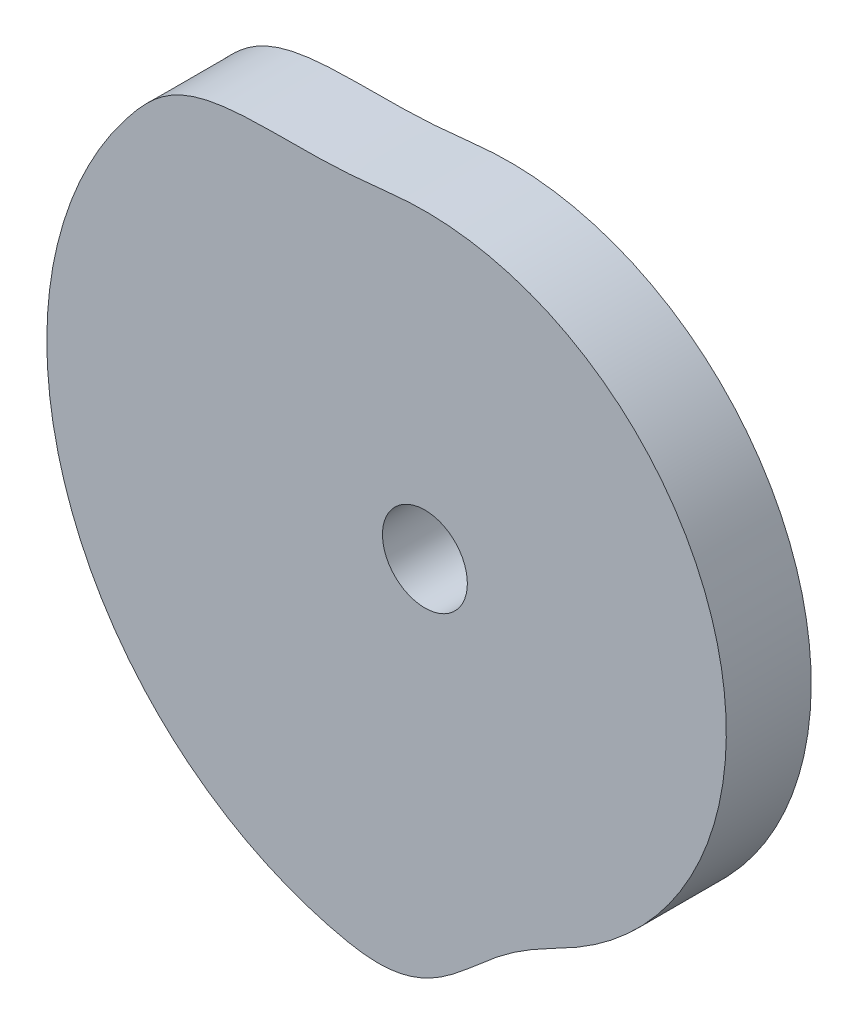
SolidWorks part; units mm, degrees
ref_plane "前视基准面" through (0, 0, 0) normal (0, 0, 1) x (1, 0, 0)
ref_plane "上视基准面" through (0, 0, 0) normal (0, 1, 0) x (1, 0, 0)
ref_plane "右视基准面" through (0, 0, 0) normal (1, 0, 0) x (0, 0, -1)
other "Configuration Table"
curve "曲线1"
sketch "草图1" plane through (0, 0, 0) normal (0, 0, 1) x (1, 0, 0)
  circle A0 centre (0, 0) radius 10
  spline S0 degree 3 poles (-56.2429, -69.0639) (-55.6381, -69.5522) (-55.029, -70.0349) (-54.4158, -70.5126) (-53.7983, -70.9847) (-53.1769, -71.4515) (-52.5513, -71.9128) (-51.9218, -72.3687) (-51.2882, -72.819) (-50.6509, -73.2638) (-50.0096, -73.7031) (-49.3645, -74.1366) (-48.7157, -74.5647) (-48.0631, -74.9868) (-47.4069, -75.4035) (-46.7471, -75.8142) (-46.0838, -76.2194) (-45.4169, -76.6186) (-44.7465, -77.0119) (-44.0728, -77.3996) (-43.3956, -77.7811) (-42.7153, -78.157) (-42.0315, -78.5266) (-41.3447, -78.8905) (-40.6547, -79.2483) (-39.9616, -79.6001) (-39.2654, -79.9458) (-38.5663, -80.2855) (-37.8642, -80.6188) (-37.1593, -80.9463) (-36.4515, -81.2674) (-35.7409, -81.5824) (-35.0276, -81.8912) (-34.3116, -82.1937) (-33.593, -82.49) (-32.8719, -82.7801) (-32.1483, -83.0638) (-31.4222, -83.3412) (-30.6937, -83.6121) (-29.9629, -83.8769) (-29.2298, -84.1352) (-28.4944, -84.3869) (-27.757, -84.6325) (-27.0174, -84.8715) (-26.2757, -85.104) (-25.532, -85.3299) (-24.7865, -85.5496) (-24.039, -85.7626) (-23.2896, -85.969) (-22.5385, -86.1691) (-21.786, -86.3624) (-21.034, -86.5486) (-20.2861, -86.7271) (-19.5453, -86.8959) (-18.8136, -87.0543) (-18.0909, -87.2016) (-17.3772, -87.3372) (-16.6721, -87.4607) (-15.9755, -87.5715) (-15.287, -87.6696) (-14.6064, -87.7543) (-13.9335, -87.8256) (-13.2677, -87.883) (-12.6088, -87.9264) (-11.9564, -87.9558) (-11.3101, -87.9707) (-10.6696, -87.9711) (-10.0343, -87.9568) (-9.404, -87.9279) (-8.7782, -87.8839) (-8.1565, -87.8251) (-7.5386, -87.751) (-6.9241, -87.6615) (-6.3127, -87.5569) (-5.7042, -87.4366) (-5.0982, -87.301) (-4.4948, -87.1496) (-3.8935, -86.9826) (-3.2945, -86.7998) (-2.6974, -86.6014) (-2.1025, -86.3873) (-1.5097, -86.1574) (-0.9189, -85.9123) (-0.3303, -85.6516) (0.256, -85.3757) (0.8402, -85.0849) (1.4219, -84.7793) (2.0013, -84.4596) (2.578, -84.1255) (3.1525, -83.7781) (3.7243, -83.4171) (4.2938, -83.0435) (4.861, -82.6576) (5.426, -82.26) (5.9889, -81.8509) (6.55, -81.4311) (7.1099, -81.0014) (7.6685, -80.5617) (8.2267, -80.1134) (8.7845, -79.6564) (9.3428, -79.1917) (9.9021, -78.72) (10.4629, -78.2415) (11.026, -77.7573) (11.592, -77.2678) (12.1617, -76.774) (12.7356, -76.2764) (13.3146, -75.7761) (13.899, -75.2735) (14.4897, -74.77) (15.0869, -74.266) (15.6913, -73.763) (16.303, -73.2615) (16.9221, -72.7629) (17.5488, -72.268) (18.1829, -71.778) (18.8241, -71.2936) (19.472, -70.816) (20.126, -70.3459) (20.7856, -69.8842) (21.4498, -69.4313) (22.1178, -68.988) (22.7886, -68.5546) (23.4613, -68.1313) (24.1346, -67.718) (24.8078, -67.3151) (25.4796, -66.9222) (26.1491, -66.539) (26.8153, -66.1652) (27.4771, -65.8001) (28.1338, -65.4437) (28.7842, -65.0948) (29.4278, -64.7532) (30.0636, -64.4182) (30.6908, -64.0889) (31.3088, -63.7649) (31.9165, -63.4455) (32.5136, -63.1302) (33.0992, -62.8184) (33.6726, -62.5094) (34.2334, -62.2029) (34.7831, -61.8972) (35.3245, -61.5898) (35.8609, -61.2791) (36.3943, -60.9637) (36.9249, -60.6439) (37.4528, -60.3194) (37.9777, -59.9901) (38.4998, -59.6565) (39.0189, -59.3183) (39.535, -58.9755) (40.0482, -58.6283) (40.5583, -58.2765) (41.0653, -57.9205) (41.5691, -57.5598) (42.0699, -57.1949) (42.5674, -56.8256) (43.0616, -56.4519) (43.5527, -56.074) (44.0403, -55.6918) (44.5247, -55.3054) (45.0055, -54.9147) (45.4831, -54.5199) (45.9571, -54.1208) (46.4277, -53.7178) (46.8947, -53.3106) (47.3581, -52.8994) (47.8179, -52.4841) (48.2741, -52.0648) (48.7266, -51.6415) (49.1754, -51.2144) (49.6204, -50.7832) (50.0618, -50.3484) (50.4991, -49.9095) (50.9327, -49.4669) (51.3626, -49.0207) (51.7884, -48.5705) (52.2102, -48.1167) (52.6282, -47.6593) (53.0421, -47.1982) (53.4519, -46.7335) (53.8577, -46.2653) (54.2594, -45.7936) (54.6568, -45.3183) (55.0503, -44.8397) (55.4395, -44.3576) (55.8245, -43.8721) (56.2053, -43.3833) (56.5815, -42.891) (56.9539, -42.3957) (57.3216, -41.897) (57.685, -41.3952) (58.0441, -40.8903) (58.3986, -40.3822) (58.7488, -39.871) (59.0946, -39.3569) (59.4358, -38.8397) (59.7724, -38.3195) (60.1046, -37.7965) (60.432, -37.2705) (60.7551, -36.7418) (61.0734, -36.2102) (61.387, -35.6758) (61.696, -35.1388) (62.0003, -34.599) (62.2999, -34.0567) (62.5947, -33.5117) (62.8847, -32.9642) (63.17, -32.4142) (63.4505, -31.8617) (63.7261, -31.3068) (63.9968, -30.7495) (64.2627, -30.1898) (64.5237, -29.6279) (64.7798, -29.0637) (65.031, -28.4973) (65.2772, -27.9287) (65.5184, -27.3579) (65.7548, -26.7852) (65.9859, -26.2103) (66.2122, -25.6335) (66.4333, -25.0548) (66.6495, -24.4741) (66.8604, -23.8915) (67.0665, -23.3072) (67.2672, -22.721) (67.463, -22.1331) (67.6536, -21.5436) (67.8389, -20.9523) (68.0193, -20.3596) (68.1943, -19.7652) (68.3642, -19.1694) (68.5289, -18.572) (68.6884, -17.9733) (68.8425, -17.3732) (68.9916, -16.7718) (69.1352, -16.1691) (69.2738, -15.5652) (69.407, -14.9601) (69.5349, -14.3538) (69.6575, -13.7465) (69.7748, -13.1381) (69.8868, -12.5287) (69.9933, -11.9183) (70.0948, -11.3071) (70.1908, -10.695) (70.2814, -10.082) (70.3667, -9.4683) (70.4467, -8.8539) (70.5213, -8.2388) (70.5905, -7.6231) (70.6543, -7.0068) (70.7128, -6.39) (70.7658, -5.7727) (70.8135, -5.1549) (70.8558, -4.5368) (70.8927, -3.9182) (70.9242, -3.2995) (70.9503, -2.6804) (70.971, -2.0611) (70.9863, -1.4417) (70.9961, -0.8222) (71.0006, -0.2027) (70.9997, 0.4169) (70.9933, 1.0365) (70.9817, 1.656) (70.9643, 2.2754) (70.9419, 2.8945) (70.9139, 3.5135) (70.8806, 4.1322) (70.8418, 4.7505) (70.7976, 5.3686) (70.7481, 5.9862) (70.6932, 6.6034) (70.6329, 7.22) (70.5672, 7.8361) (70.4961, 8.4516) (70.4197, 9.0665) (70.3379, 9.6807) (70.2507, 10.2941) (70.1582, 10.9068) (70.0602, 11.5186) (69.9572, 12.1296) (69.8485, 12.7395) (69.7348, 13.3486) (69.6157, 13.9566) (69.4911, 14.5636) (69.3615, 15.1695) (69.2265, 15.7742) (69.0862, 16.3777) (68.9405, 16.9799) (68.7898, 17.5809) (68.6338, 18.1806) (68.4724, 18.7788) (68.3061, 19.3757) (68.1344, 19.971) (67.9575, 20.5647) (67.7754, 21.157) (67.5883, 21.7477) (67.3959, 22.3367) (67.1983, 22.9239) (66.9958, 23.5095) (66.788, 24.0932) (66.5752, 24.6751) (66.3574, 25.2551) (66.1345, 25.8333) (65.9066, 26.4094) (65.6735, 26.9835) (65.4356, 27.5556) (65.1926, 28.1255) (64.9447, 28.6934) (64.6918, 29.259) (64.434, 29.8225) (64.1713, 30.3836) (63.9039, 30.9425) (63.6313, 31.499) (63.354, 32.053) (63.0719, 32.6047) (62.785, 33.1538) (62.4933, 33.7005) (62.1968, 34.2445) (61.8956, 34.7859) (61.5897, 35.3248) (61.2791, 35.8609) (60.9637, 36.3943) (60.6439, 36.9249) (60.3194, 37.4528) (59.9901, 37.9777) (59.6565, 38.4998) (59.3183, 39.0189) (58.9755, 39.535) (58.6283, 40.0482) (58.2765, 40.5583) (57.9205, 41.0653) (57.5598, 41.5691) (57.1949, 42.0699) (56.8256, 42.5674) (56.4519, 43.0616) (56.074, 43.5527) (55.6918, 44.0403) (55.3054, 44.5247) (54.9147, 45.0055) (54.5199, 45.4831) (54.1208, 45.9571) (53.7178, 46.4277) (53.3106, 46.8947) (52.8994, 47.3581) (52.4841, 47.8179) (52.0648, 48.2741) (51.6415, 48.7266) (51.2144, 49.1754) (50.7832, 49.6204) (50.3484, 50.0618) (49.9095, 50.4991) (49.4669, 50.9327) (49.0207, 51.3626) (48.5705, 51.7884) (48.1167, 52.2102) (47.6593, 52.6282) (47.1982, 53.0421) (46.7335, 53.4519) (46.2653, 53.8577) (45.7936, 54.2594) (45.3183, 54.6568) (44.8397, 55.0503) (44.3576, 55.4395) (43.8721, 55.8245) (43.3833, 56.2053) (42.891, 56.5815) (42.3957, 56.9539) (41.897, 57.3216) (41.3952, 57.685) (40.8903, 58.0441) (40.3822, 58.3986) (39.871, 58.7488) (39.3569, 59.0946) (38.8397, 59.4358) (38.3195, 59.7724) (37.7965, 60.1046) (37.2705, 60.432) (36.7418, 60.7551) (36.2102, 61.0734) (35.6758, 61.387) (35.1388, 61.696) (34.599, 62.0003) (34.0567, 62.2999) (33.5117, 62.5947) (32.9642, 62.8847) (32.4142, 63.17) (31.8617, 63.4505) (31.3068, 63.7261) (30.7495, 63.9968) (30.1898, 64.2627) (29.6279, 64.5237) (29.0637, 64.7798) (28.4973, 65.031) (27.9287, 65.2772) (27.3579, 65.5184) (26.7852, 65.7548) (26.2103, 65.9859) (25.6335, 66.2122) (25.0548, 66.4333) (24.4741, 66.6495) (23.8915, 66.8604) (23.3072, 67.0665) (22.721, 67.2672) (22.1331, 67.463) (21.5436, 67.6536) (20.9523, 67.8389) (20.3596, 68.0193) (19.7652, 68.1943) (19.1694, 68.3642) (18.572, 68.5289) (17.9733, 68.6884) (17.3732, 68.8425) (16.7718, 68.9916) (16.1691, 69.1352) (15.5652, 69.2738) (14.9601, 69.407) (14.3538, 69.5349) (13.7465, 69.6575) (13.1381, 69.7748) (12.5287, 69.8868) (11.9183, 69.9933) (11.3071, 70.0948) (10.695, 70.1908) (10.082, 70.2814) (9.4683, 70.3667) (8.8539, 70.4467) (8.2388, 70.5213) (7.6231, 70.5905) (7.0068, 70.6543) (6.39, 70.7128) (5.7727, 70.7658) (5.1549, 70.8135) (4.5368, 70.8558) (3.9182, 70.8927) (3.2995, 70.9242) (2.6804, 70.9503) (2.0611, 70.971) (1.4417, 70.9863) (0.8222, 70.9961) (0.2027, 71.0006) (-0.4169, 70.9997) (-1.0365, 70.9933) (-1.656, 70.9817) (-2.2754, 70.9643) (-2.8945, 70.9419) (-3.5135, 70.9139) (-4.1322, 70.8806) (-4.7509, 70.8417) (-5.3719, 70.7975) (-5.9991, 70.747) (-6.6367, 70.6912) (-7.287, 70.63) (-7.9506, 70.5644) (-8.6275, 70.4953) (-9.3177, 70.4227) (-10.0212, 70.3482) (-10.7377, 70.2719) (-11.4671, 70.195) (-12.2091, 70.1178) (-12.9634, 70.0417) (-13.7294, 69.9665) (-14.507, 69.8936) (-15.2956, 69.8231) (-16.0946, 69.7559) (-16.9037, 69.6919) (-17.7223, 69.632) (-18.5498, 69.5763) (-19.3858, 69.5249) (-20.2297, 69.4781) (-21.0811, 69.4361) (-21.9393, 69.3985) (-22.804, 69.3656) (-23.6745, 69.3369) (-24.5504, 69.3125) (-25.4313, 69.2921) (-26.3165, 69.2752) (-27.2056, 69.2616) (-28.098, 69.2509) (-28.9932, 69.2424) (-29.8907, 69.2361) (-30.7898, 69.231) (-31.6899, 69.227) (-32.5905, 69.223) (-33.4908, 69.219) (-34.3901, 69.2138) (-35.2878, 69.2072) (-36.1831, 69.1986) (-37.0751, 69.1869) (-37.9632, 69.1722) (-38.8465, 69.153) (-39.7241, 69.1293) (-40.5954, 69.1002) (-41.4594, 69.0653) (-42.3153, 69.0237) (-43.1623, 68.9751) (-43.9997, 68.9188) (-44.8265, 68.8545) (-45.6422, 68.7815) (-46.4461, 68.6996) (-47.2374, 68.6081) (-48.0157, 68.507) (-48.7803, 68.3959) (-49.531, 68.2744) (-50.2672, 68.1423) (-50.9887, 67.9995) (-51.6956, 67.846) (-52.3875, 67.6814) (-53.0646, 67.5056) (-53.727, 67.3188) (-54.375, 67.1206) (-55.0089, 66.9111) (-55.6291, 66.6901) (-56.2362, 66.4577) (-56.8306, 66.2135) (-57.4132, 65.9575) (-57.9846, 65.6893) (-58.5455, 65.409) (-59.0967, 65.116) (-59.6389, 64.8103) (-60.173, 64.4915) (-60.6994, 64.1591) (-61.2194, 63.8131) (-61.7331, 63.4529) (-62.2415, 63.0783) (-62.7451, 62.689) (-63.2444, 62.2847) (-63.74, 61.8653) (-64.2324, 61.4304) (-64.7219, 60.98) (-65.2092, 60.5139) (-65.6945, 60.0323) (-66.1783, 59.5351) (-66.6609, 59.0224) (-67.1427, 58.4943) (-67.6244, 57.9512) (-68.106, 57.3932) (-68.5881, 56.8206) (-69.071, 56.2342) (-69.554, 55.6359) (-70.0351, 55.0287) (-70.5126, 54.4158) (-70.9847, 53.7983) (-71.4515, 53.1769) (-71.9128, 52.5513) (-72.3687, 51.9218) (-72.819, 51.2882) (-73.2638, 50.6509) (-73.7031, 50.0096) (-74.1366, 49.3645) (-74.5647, 48.7157) (-74.9868, 48.0631) (-75.4035, 47.4069) (-75.8142, 46.7471) (-76.2194, 46.0838) (-76.6186, 45.4169) (-77.0119, 44.7465) (-77.3996, 44.0728) (-77.7811, 43.3956) (-78.157, 42.7153) (-78.5266, 42.0315) (-78.8905, 41.3447) (-79.2483, 40.6547) (-79.6001, 39.9616) (-79.9458, 39.2654) (-80.2855, 38.5663) (-80.6188, 37.8642) (-80.9463, 37.1593) (-81.2674, 36.4515) (-81.5824, 35.7409) (-81.8912, 35.0276) (-82.1937, 34.3116) (-82.49, 33.593) (-82.7801, 32.8719) (-83.0638, 32.1483) (-83.3412, 31.4222) (-83.6121, 30.6937) (-83.8769, 29.9629) (-84.1352, 29.2298) (-84.3869, 28.4944) (-84.6325, 27.757) (-84.8715, 27.0174) (-85.104, 26.2757) (-85.3299, 25.532) (-85.5496, 24.7865) (-85.7626, 24.039) (-85.969, 23.2896) (-86.1691, 22.5385) (-86.3625, 21.7857) (-86.5493, 21.0312) (-86.7296, 20.2752) (-86.9032, 19.5175) (-87.0702, 18.7584) (-87.2306, 17.9979) (-87.3843, 17.236) (-87.5314, 16.4728) (-87.6718, 15.7083) (-87.8057, 14.9427) (-87.9326, 14.1759) (-88.053, 13.408) (-88.1666, 12.639) (-88.2735, 11.8692) (-88.3739, 11.0984) (-88.4672, 10.3267) (-88.5541, 9.5543) (-88.634, 8.7812) (-88.7073, 8.0074) (-88.7738, 7.233) (-88.8335, 6.458) (-88.8865, 5.6826) (-88.9327, 4.9067) (-88.9721, 4.1305) (-89.0049, 3.3539) (-89.0306, 2.577) (-89.0498, 1.8) (-89.062, 1.0228) (-89.0677, 0.2456) (-89.0663, -0.5317) (-89.0583, -1.3089) (-89.0435, -2.086) (-89.0219, -2.8629) (-88.9935, -3.6397) (-88.9584, -4.4161) (-88.9165, -5.1923) (-88.8678, -5.968) (-88.8123, -6.7433) (-88.7501, -7.5181) (-88.6812, -8.2923) (-88.6053, -9.0658) (-88.523, -9.8387) (-88.4336, -10.6108) (-88.3378, -11.3821) (-88.235, -12.1526) (-88.1256, -12.9221) (-88.0095, -13.6907) (-87.8866, -14.4582) (-87.7571, -15.2246) (-87.6209, -15.9898) (-87.478, -16.7538) (-87.3285, -17.5165) (-87.1723, -18.2779) (-87.0095, -19.038) (-86.8401, -19.7965) (-86.664, -20.5536) (-86.4813, -21.3091) (-86.2921, -22.063) (-86.0963, -22.8152) (-85.8939, -23.5656) (-85.685, -24.3143) (-85.4696, -25.0611) (-85.2475, -25.806) (-85.0192, -26.5489) (-84.7843, -27.2898) (-84.5429, -28.0287) (-84.2951, -28.7654) (-84.0409, -29.4999) (-83.7801, -30.2321) (-83.5132, -30.9621) (-83.2397, -31.6897) (-82.9601, -32.4149) (-82.674, -33.1376) (-82.3818, -33.8578) (-82.0831, -34.5754) (-81.7783, -35.2904) (-81.4672, -36.0027) (-81.15, -36.7122) (-80.8264, -37.419) (-80.4968, -38.1229) (-80.1611, -38.8239) (-79.8192, -39.522) (-79.4713, -40.217) (-79.1173, -40.909) (-78.7573, -41.5978) (-78.3913, -42.2835) (-78.0194, -42.9661) (-77.6415, -43.6453) (-77.2575, -44.3211) (-76.8679, -44.9936) (-76.4724, -45.6627) (-76.071, -46.3283) (-75.6638, -46.9904) (-75.2508, -47.6488) (-74.8322, -48.3037) (-74.4078, -48.9549) (-73.9777, -49.6024) (-73.542, -50.246) (-73.1008, -50.8859) (-72.6539, -51.5218) (-72.2017, -52.154) (-71.7437, -52.782) (-71.2804, -53.4061) (-70.8116, -54.0261) (-70.3375, -54.642) (-69.858, -55.2537) (-69.3731, -55.8612) (-68.8829, -56.4644) (-68.3877, -57.0635) (-67.8871, -57.658) (-67.3813, -58.2483) (-66.8705, -58.834) (-66.3544, -59.4153) (-65.8334, -59.9922) (-65.3074, -60.5644) (-64.7764, -61.132) (-64.2405, -61.6949) (-63.6997, -62.2531) (-63.154, -62.8066) (-62.6035, -63.3554) (-62.0483, -63.8993) (-61.4883, -64.4383) (-60.9236, -64.9724) (-60.3543, -65.5016) (-59.7804, -66.0258) (-59.2019, -66.545) (-58.6189, -67.059) (-58.0316, -67.5681) (-57.4397, -68.0719) (-56.8435, -68.5706) (-56.2429, -69.0639) (-55.6381, -69.5522) (-55.029, -70.0349) knots -0.004634 -0.00309 -0.001545 0 0.001545 0.003089 0.004634 0.006179 0.007724 0.009269 0.010813 0.012358 0.013903 0.015447 0.016992 0.018537 0.020082 0.021626 0.023171 0.024716 0.026261 0.027805 0.02935 0.030895 0.03244 0.033984 0.035529 0.037074 0.038619 0.040163 0.041708 0.043253 0.044798 0.046342 0.047887 0.049432 0.050977 0.052521 0.054066 0.055611 0.057156 0.0587 0.060245 0.06179 0.063335 0.064879 0.066424 0.067969 0.069514 0.071058 0.072603 0.074148 0.075693 0.077236 0.078767 0.080277 0.081765 0.083231 0.084674 0.086097 0.087498 0.08888 0.090243 0.091587 0.092915 0.094227 0.095524 0.096809 0.098081 0.099343 0.100597 0.101843 0.103083 0.104319 0.105553 0.106785 0.108018 0.109251 0.110487 0.111727 0.112971 0.114221 0.115477 0.116741 0.118012 0.119291 0.120579 0.121875 0.123181 0.124496 0.125821 0.127155 0.128499 0.129852 0.131216 0.132589 0.133971 0.135364 0.136767 0.138179 0.139602 0.141036 0.142479 0.143933 0.145398 0.146874 0.148361 0.14986 0.151369 0.15289 0.154422 0.155965 0.157518 0.159081 0.160653 0.162234 0.163821 0.165414 0.167012 0.168612 0.170214 0.171814 0.173412 0.175006 0.176594 0.178174 0.179745 0.181305 0.182852 0.184385 0.185904 0.187406 0.188892 0.190359 0.191807 0.193236 0.194644 0.196031 0.197396 0.198738 0.200057 0.201351 0.202621 0.203868 0.205101 0.206333 0.207564 0.208796 0.210027 0.211259 0.21249 0.213721 0.214953 0.216184 0.217416 0.218647 0.219878 0.22111 0.222341 0.223573 0.224804 0.226035 0.227267 0.228498 0.22973 0.230961 0.232192 0.233424 0.234655 0.235887 0.237118 0.238349 0.239581 0.240812 0.242044 0.243275 0.244506 0.245738 0.246969 0.248201 0.249432 0.250663 0.251895 0.253126 0.254358 0.255589 0.25682 0.258052 0.259283 0.260515 0.261746 0.262977 0.264209 0.26544 0.266672 0.267903 0.269135 0.270366 0.271597 0.272829 0.27406 0.275292 0.276523 0.277754 0.278986 0.280217 0.281449 0.28268 0.283911 0.285143 0.286374 0.287606 0.288837 0.290068 0.2913 0.292531 0.293763 0.294994 0.296225 0.297457 0.298688 0.29992 0.301151 0.302382 0.303614 0.304845 0.306077 0.307308 0.308539 0.309771 0.311002 0.312234 0.313465 0.314696 0.315928 0.317159 0.318391 0.319622 0.320853 0.322085 0.323316 0.324548 0.325779 0.327011 0.328242 0.329473 0.330705 0.331936 0.333168 0.334399 0.33563 0.336862 0.338093 0.339325 0.340556 0.341787 0.343019 0.34425 0.345482 0.346713 0.347944 0.349176 0.350407 0.351639 0.35287 0.354101 0.355333 0.356564 0.357796 0.359027 0.360258 0.36149 0.362721 0.363953 0.365184 0.366415 0.367647 0.368878 0.37011 0.371341 0.372572 0.373804 0.375035 0.376267 0.377498 0.378729 0.379961 0.381192 0.382424 0.383655 0.384886 0.386118 0.387349 0.388581 0.389812 0.391044 0.392275 0.393506 0.394738 0.395969 0.397201 0.398432 0.399663 0.400895 0.402126 0.403358 0.404589 0.40582 0.407052 0.408283 0.409514 0.410746 0.411977 0.413209 0.41444 0.415672 0.416903 0.418134 0.419366 0.420597 0.421829 0.42306 0.424291 0.425523 0.426754 0.427986 0.429217 0.430448 0.43168 0.432911 0.434143 0.435374 0.436605 0.437837 0.439068 0.4403 0.441531 0.442762 0.443994 0.445225 0.446457 0.447688 0.448919 0.450151 0.451382 0.452614 0.453845 0.455077 0.456308 0.457539 0.458771 0.460002 0.461234 0.462465 0.463696 0.464928 0.466159 0.467391 0.468622 0.469853 0.471085 0.472316 0.473548 0.474779 0.47601 0.477242 0.478473 0.479705 0.480936 0.482167 0.483399 0.48463 0.485862 0.487093 0.488324 0.489556 0.490787 0.492019 0.49325 0.494482 0.495713 0.496944 0.498176 0.499407 0.500638 0.50187 0.503101 0.504333 0.505564 0.506795 0.508027 0.509258 0.51049 0.511721 0.512953 0.514184 0.515415 0.516647 0.517878 0.51911 0.520341 0.521572 0.522804 0.524035 0.525266 0.526498 0.527729 0.528961 0.530192 0.531424 0.532655 0.533886 0.535118 0.536349 0.537581 0.538812 0.540043 0.541275 0.542506 0.543738 0.544969 0.5462 0.547432 0.548663 0.549895 0.551126 0.552357 0.553589 0.55482 0.556052 0.557283 0.558514 0.559746 0.560977 0.562209 0.56344 0.564671 0.565903 0.567134 0.568366 0.569597 0.570829 0.57206 0.573291 0.574523 0.575754 0.576986 0.578217 0.579448 0.58068 0.581911 0.583142 0.584374 0.585607 0.586854 0.588125 0.589423 0.590749 0.592101 0.593481 0.594887 0.596319 0.597777 0.59926 0.600767 0.602297 0.603849 0.605423 0.607017 0.608631 0.610262 0.611911 0.613576 0.615256 0.61695 0.618658 0.620378 0.622109 0.623851 0.625603 0.627363 0.62913 0.630904 0.632684 0.634468 0.636255 0.638045 0.639835 0.641625 0.643413 0.645197 0.646977 0.648751 0.650517 0.652273 0.654018 0.655751 0.65747 0.659174 0.660861 0.662529 0.664178 0.665806 0.667412 0.668995 0.670555 0.672091 0.673602 0.675089 0.67655 0.677988 0.679401 0.680791 0.682158 0.683504 0.684831 0.686138 0.68743 0.688706 0.68997 0.691223 0.692469 0.693708 0.694944 0.69618 0.697416 0.698657 0.699903 0.701157 0.702421 0.703698 0.704987 0.706292 0.707614 0.708954 0.710312 0.711691 0.71309 0.71451 0.715953 0.717418 0.718905 0.720415 0.721947 0.72349 0.725034 0.726579 0.728124 0.729669 0.731214 0.732758 0.734303 0.735848 0.737392 0.738937 0.740482 0.742027 0.743571 0.745116 0.746661 0.748206 0.74975 0.751295 0.75284 0.754385 0.755929 0.757474 0.759019 0.760564 0.762108 0.763653 0.765198 0.766743 0.768288 0.769832 0.771377 0.772922 0.774466 0.776011 0.777556 0.779101 0.780646 0.78219 0.783735 0.78528 0.786824 0.788369 0.789914 0.791459 0.793003 0.794548 0.796093 0.797638 0.799182 0.800727 0.802272 0.803817 0.805361 0.806906 0.808451 0.809996 0.81154 0.813085 0.81463 0.816175 0.817719 0.819264 0.820809 0.822354 0.823899 0.825443 0.826988 0.828533 0.830078 0.831622 0.833167 0.834712 0.836256 0.837801 0.839346 0.840891 0.842435 0.84398 0.845525 0.84707 0.848614 0.850159 0.851704 0.853249 0.854793 0.856338 0.857883 0.859428 0.860972 0.862517 0.864062 0.865607 0.867152 0.868696 0.870241 0.871786 0.87333 0.874875 0.87642 0.877965 0.879509 0.881054 0.882599 0.884144 0.885688 0.887233 0.888778 0.890323 0.891868 0.893412 0.894957 0.896502 0.898046 0.899591 0.901136 0.902681 0.904225 0.90577 0.907315 0.90886 0.910405 0.911949 0.913494 0.915039 0.916584 0.918128 0.919673 0.921218 0.922763 0.924307 0.925852 0.927397 0.928941 0.930486 0.932031 0.933576 0.93512 0.936665 0.93821 0.939755 0.941299 0.942844 0.944389 0.945934 0.947478 0.949023 0.950568 0.952113 0.953657 0.955202 0.956747 0.958292 0.959836 0.961381 0.962926 0.964471 0.966015 0.96756 0.969105 0.97065 0.972195 0.973739 0.975284 0.976829 0.978373 0.979918 0.981463 0.983008 0.984552 0.986097 0.987642 0.989187 0.990731 0.992276 0.993821 0.995366 0.99691 0.998455 1 1.001545 1.003089 1.004634 only from (-55.6374, -69.5513) to (-55.6374, -69.5513) construction
  spline S1 degree 3 poles (-56.2429, -69.0639) (-55.6381, -69.5522) (-55.029, -70.0349) (-54.4158, -70.5126) (-53.7983, -70.9847) (-53.1769, -71.4515) (-52.5513, -71.9128) (-51.9218, -72.3687) (-51.2882, -72.819) (-50.6509, -73.2638) (-50.0096, -73.7031) (-49.3645, -74.1366) (-48.7157, -74.5647) (-48.0631, -74.9868) (-47.4069, -75.4035) (-46.7471, -75.8142) (-46.0838, -76.2194) (-45.4169, -76.6186) (-44.7465, -77.0119) (-44.0728, -77.3996) (-43.3956, -77.7811) (-42.7153, -78.157) (-42.0315, -78.5266) (-41.3447, -78.8905) (-40.6547, -79.2483) (-39.9616, -79.6001) (-39.2654, -79.9458) (-38.5663, -80.2855) (-37.8642, -80.6188) (-37.1593, -80.9463) (-36.4515, -81.2674) (-35.7409, -81.5824) (-35.0276, -81.8912) (-34.3116, -82.1937) (-33.593, -82.49) (-32.8719, -82.7801) (-32.1483, -83.0638) (-31.4222, -83.3412) (-30.6937, -83.6121) (-29.9629, -83.8769) (-29.2298, -84.1352) (-28.4944, -84.3869) (-27.757, -84.6325) (-27.0174, -84.8715) (-26.2757, -85.104) (-25.532, -85.3299) (-24.7865, -85.5496) (-24.039, -85.7626) (-23.2896, -85.969) (-22.5385, -86.1691) (-21.786, -86.3624) (-21.034, -86.5486) (-20.2861, -86.7271) (-19.5453, -86.8959) (-18.8136, -87.0543) (-18.0909, -87.2016) (-17.3772, -87.3372) (-16.6721, -87.4607) (-15.9755, -87.5715) (-15.287, -87.6696) (-14.6064, -87.7543) (-13.9335, -87.8256) (-13.2677, -87.883) (-12.6088, -87.9264) (-11.9564, -87.9558) (-11.3101, -87.9707) (-10.6696, -87.9711) (-10.0343, -87.9568) (-9.404, -87.9279) (-8.7782, -87.8839) (-8.1565, -87.8251) (-7.5386, -87.751) (-6.9241, -87.6615) (-6.3127, -87.5569) (-5.7042, -87.4366) (-5.0982, -87.301) (-4.4948, -87.1496) (-3.8935, -86.9826) (-3.2945, -86.7998) (-2.6974, -86.6014) (-2.1025, -86.3873) (-1.5097, -86.1574) (-0.9189, -85.9123) (-0.3303, -85.6516) (0.256, -85.3757) (0.8402, -85.0849) (1.4219, -84.7793) (2.0013, -84.4596) (2.578, -84.1255) (3.1525, -83.7781) (3.7243, -83.4171) (4.2938, -83.0435) (4.861, -82.6576) (5.426, -82.26) (5.9889, -81.8509) (6.55, -81.4311) (7.1099, -81.0014) (7.6685, -80.5617) (8.2267, -80.1134) (8.7845, -79.6564) (9.3428, -79.1917) (9.9021, -78.72) (10.4629, -78.2415) (11.026, -77.7573) (11.592, -77.2678) (12.1617, -76.774) (12.7356, -76.2764) (13.3146, -75.7761) (13.899, -75.2735) (14.4897, -74.77) (15.0869, -74.266) (15.6913, -73.763) (16.303, -73.2615) (16.9221, -72.7629) (17.5488, -72.268) (18.1829, -71.778) (18.8241, -71.2936) (19.472, -70.816) (20.126, -70.3459) (20.7856, -69.8842) (21.4498, -69.4313) (22.1178, -68.988) (22.7886, -68.5546) (23.4613, -68.1313) (24.1346, -67.718) (24.8078, -67.3151) (25.4796, -66.9222) (26.1491, -66.539) (26.8153, -66.1652) (27.4771, -65.8001) (28.1338, -65.4437) (28.7842, -65.0948) (29.4278, -64.7532) (30.0636, -64.4182) (30.6908, -64.0889) (31.3088, -63.7649) (31.9165, -63.4455) (32.5136, -63.1302) (33.0992, -62.8184) (33.6726, -62.5094) (34.2334, -62.2029) (34.7831, -61.8972) (35.3245, -61.5898) (35.8609, -61.2791) (36.3943, -60.9637) (36.9249, -60.6439) (37.4528, -60.3194) (37.9777, -59.9901) (38.4998, -59.6565) (39.0189, -59.3183) (39.535, -58.9755) (40.0482, -58.6283) (40.5583, -58.2765) (41.0653, -57.9205) (41.5691, -57.5598) (42.0699, -57.1949) (42.5674, -56.8256) (43.0616, -56.4519) (43.5527, -56.074) (44.0403, -55.6918) (44.5247, -55.3054) (45.0055, -54.9147) (45.4831, -54.5199) (45.9571, -54.1208) (46.4277, -53.7178) (46.8947, -53.3106) (47.3581, -52.8994) (47.8179, -52.4841) (48.2741, -52.0648) (48.7266, -51.6415) (49.1754, -51.2144) (49.6204, -50.7832) (50.0618, -50.3484) (50.4991, -49.9095) (50.9327, -49.4669) (51.3626, -49.0207) (51.7884, -48.5705) (52.2102, -48.1167) (52.6282, -47.6593) (53.0421, -47.1982) (53.4519, -46.7335) (53.8577, -46.2653) (54.2594, -45.7936) (54.6568, -45.3183) (55.0503, -44.8397) (55.4395, -44.3576) (55.8245, -43.8721) (56.2053, -43.3833) (56.5815, -42.891) (56.9539, -42.3957) (57.3216, -41.897) (57.685, -41.3952) (58.0441, -40.8903) (58.3986, -40.3822) (58.7488, -39.871) (59.0946, -39.3569) (59.4358, -38.8397) (59.7724, -38.3195) (60.1046, -37.7965) (60.432, -37.2705) (60.7551, -36.7418) (61.0734, -36.2102) (61.387, -35.6758) (61.696, -35.1388) (62.0003, -34.599) (62.2999, -34.0567) (62.5947, -33.5117) (62.8847, -32.9642) (63.17, -32.4142) (63.4505, -31.8617) (63.7261, -31.3068) (63.9968, -30.7495) (64.2627, -30.1898) (64.5237, -29.6279) (64.7798, -29.0637) (65.031, -28.4973) (65.2772, -27.9287) (65.5184, -27.3579) (65.7548, -26.7852) (65.9859, -26.2103) (66.2122, -25.6335) (66.4333, -25.0548) (66.6495, -24.4741) (66.8604, -23.8915) (67.0665, -23.3072) (67.2672, -22.721) (67.463, -22.1331) (67.6536, -21.5436) (67.8389, -20.9523) (68.0193, -20.3596) (68.1943, -19.7652) (68.3642, -19.1694) (68.5289, -18.572) (68.6884, -17.9733) (68.8425, -17.3732) (68.9916, -16.7718) (69.1352, -16.1691) (69.2738, -15.5652) (69.407, -14.9601) (69.5349, -14.3538) (69.6575, -13.7465) (69.7748, -13.1381) (69.8868, -12.5287) (69.9933, -11.9183) (70.0948, -11.3071) (70.1908, -10.695) (70.2814, -10.082) (70.3667, -9.4683) (70.4467, -8.8539) (70.5213, -8.2388) (70.5905, -7.6231) (70.6543, -7.0068) (70.7128, -6.39) (70.7658, -5.7727) (70.8135, -5.1549) (70.8558, -4.5368) (70.8927, -3.9182) (70.9242, -3.2995) (70.9503, -2.6804) (70.971, -2.0611) (70.9863, -1.4417) (70.9961, -0.8222) (71.0006, -0.2027) (70.9997, 0.4169) (70.9933, 1.0365) (70.9817, 1.656) (70.9643, 2.2754) (70.9419, 2.8945) (70.9139, 3.5135) (70.8806, 4.1322) (70.8418, 4.7505) (70.7976, 5.3686) (70.7481, 5.9862) (70.6932, 6.6034) (70.6329, 7.22) (70.5672, 7.8361) (70.4961, 8.4516) (70.4197, 9.0665) (70.3379, 9.6807) (70.2507, 10.2941) (70.1582, 10.9068) (70.0602, 11.5186) (69.9572, 12.1296) (69.8485, 12.7395) (69.7348, 13.3486) (69.6157, 13.9566) (69.4911, 14.5636) (69.3615, 15.1695) (69.2265, 15.7742) (69.0862, 16.3777) (68.9405, 16.9799) (68.7898, 17.5809) (68.6338, 18.1806) (68.4724, 18.7788) (68.3061, 19.3757) (68.1344, 19.971) (67.9575, 20.5647) (67.7754, 21.157) (67.5883, 21.7477) (67.3959, 22.3367) (67.1983, 22.9239) (66.9958, 23.5095) (66.788, 24.0932) (66.5752, 24.6751) (66.3574, 25.2551) (66.1345, 25.8333) (65.9066, 26.4094) (65.6735, 26.9835) (65.4356, 27.5556) (65.1926, 28.1255) (64.9447, 28.6934) (64.6918, 29.259) (64.434, 29.8225) (64.1713, 30.3836) (63.9039, 30.9425) (63.6313, 31.499) (63.354, 32.053) (63.0719, 32.6047) (62.785, 33.1538) (62.4933, 33.7005) (62.1968, 34.2445) (61.8956, 34.7859) (61.5897, 35.3248) (61.2791, 35.8609) (60.9637, 36.3943) (60.6439, 36.9249) (60.3194, 37.4528) (59.9901, 37.9777) (59.6565, 38.4998) (59.3183, 39.0189) (58.9755, 39.535) (58.6283, 40.0482) (58.2765, 40.5583) (57.9205, 41.0653) (57.5598, 41.5691) (57.1949, 42.0699) (56.8256, 42.5674) (56.4519, 43.0616) (56.074, 43.5527) (55.6918, 44.0403) (55.3054, 44.5247) (54.9147, 45.0055) (54.5199, 45.4831) (54.1208, 45.9571) (53.7178, 46.4277) (53.3106, 46.8947) (52.8994, 47.3581) (52.4841, 47.8179) (52.0648, 48.2741) (51.6415, 48.7266) (51.2144, 49.1754) (50.7832, 49.6204) (50.3484, 50.0618) (49.9095, 50.4991) (49.4669, 50.9327) (49.0207, 51.3626) (48.5705, 51.7884) (48.1167, 52.2102) (47.6593, 52.6282) (47.1982, 53.0421) (46.7335, 53.4519) (46.2653, 53.8577) (45.7936, 54.2594) (45.3183, 54.6568) (44.8397, 55.0503) (44.3576, 55.4395) (43.8721, 55.8245) (43.3833, 56.2053) (42.891, 56.5815) (42.3957, 56.9539) (41.897, 57.3216) (41.3952, 57.685) (40.8903, 58.0441) (40.3822, 58.3986) (39.871, 58.7488) (39.3569, 59.0946) (38.8397, 59.4358) (38.3195, 59.7724) (37.7965, 60.1046) (37.2705, 60.432) (36.7418, 60.7551) (36.2102, 61.0734) (35.6758, 61.387) (35.1388, 61.696) (34.599, 62.0003) (34.0567, 62.2999) (33.5117, 62.5947) (32.9642, 62.8847) (32.4142, 63.17) (31.8617, 63.4505) (31.3068, 63.7261) (30.7495, 63.9968) (30.1898, 64.2627) (29.6279, 64.5237) (29.0637, 64.7798) (28.4973, 65.031) (27.9287, 65.2772) (27.3579, 65.5184) (26.7852, 65.7548) (26.2103, 65.9859) (25.6335, 66.2122) (25.0548, 66.4333) (24.4741, 66.6495) (23.8915, 66.8604) (23.3072, 67.0665) (22.721, 67.2672) (22.1331, 67.463) (21.5436, 67.6536) (20.9523, 67.8389) (20.3596, 68.0193) (19.7652, 68.1943) (19.1694, 68.3642) (18.572, 68.5289) (17.9733, 68.6884) (17.3732, 68.8425) (16.7718, 68.9916) (16.1691, 69.1352) (15.5652, 69.2738) (14.9601, 69.407) (14.3538, 69.5349) (13.7465, 69.6575) (13.1381, 69.7748) (12.5287, 69.8868) (11.9183, 69.9933) (11.3071, 70.0948) (10.695, 70.1908) (10.082, 70.2814) (9.4683, 70.3667) (8.8539, 70.4467) (8.2388, 70.5213) (7.6231, 70.5905) (7.0068, 70.6543) (6.39, 70.7128) (5.7727, 70.7658) (5.1549, 70.8135) (4.5368, 70.8558) (3.9182, 70.8927) (3.2995, 70.9242) (2.6804, 70.9503) (2.0611, 70.971) (1.4417, 70.9863) (0.8222, 70.9961) (0.2027, 71.0006) (-0.4169, 70.9997) (-1.0365, 70.9933) (-1.656, 70.9817) (-2.2754, 70.9643) (-2.8945, 70.9419) (-3.5135, 70.9139) (-4.1322, 70.8806) (-4.7509, 70.8417) (-5.3719, 70.7975) (-5.9991, 70.747) (-6.6367, 70.6912) (-7.287, 70.63) (-7.9506, 70.5644) (-8.6275, 70.4953) (-9.3177, 70.4227) (-10.0212, 70.3482) (-10.7377, 70.2719) (-11.4671, 70.195) (-12.2091, 70.1178) (-12.9634, 70.0417) (-13.7294, 69.9665) (-14.507, 69.8936) (-15.2956, 69.8231) (-16.0946, 69.7559) (-16.9037, 69.6919) (-17.7223, 69.632) (-18.5498, 69.5763) (-19.3858, 69.5249) (-20.2297, 69.4781) (-21.0811, 69.4361) (-21.9393, 69.3985) (-22.804, 69.3656) (-23.6745, 69.3369) (-24.5504, 69.3125) (-25.4313, 69.2921) (-26.3165, 69.2752) (-27.2056, 69.2616) (-28.098, 69.2509) (-28.9932, 69.2424) (-29.8907, 69.2361) (-30.7898, 69.231) (-31.6899, 69.227) (-32.5905, 69.223) (-33.4908, 69.219) (-34.3901, 69.2138) (-35.2878, 69.2072) (-36.1831, 69.1986) (-37.0751, 69.1869) (-37.9632, 69.1722) (-38.8465, 69.153) (-39.7241, 69.1293) (-40.5954, 69.1002) (-41.4594, 69.0653) (-42.3153, 69.0237) (-43.1623, 68.9751) (-43.9997, 68.9188) (-44.8265, 68.8545) (-45.6422, 68.7815) (-46.4461, 68.6996) (-47.2374, 68.6081) (-48.0157, 68.507) (-48.7803, 68.3959) (-49.531, 68.2744) (-50.2672, 68.1423) (-50.9887, 67.9995) (-51.6956, 67.846) (-52.3875, 67.6814) (-53.0646, 67.5056) (-53.727, 67.3188) (-54.375, 67.1206) (-55.0089, 66.9111) (-55.6291, 66.6901) (-56.2362, 66.4577) (-56.8306, 66.2135) (-57.4132, 65.9575) (-57.9846, 65.6893) (-58.5455, 65.409) (-59.0967, 65.116) (-59.6389, 64.8103) (-60.173, 64.4915) (-60.6994, 64.1591) (-61.2194, 63.8131) (-61.7331, 63.4529) (-62.2415, 63.0783) (-62.7451, 62.689) (-63.2444, 62.2847) (-63.74, 61.8653) (-64.2324, 61.4304) (-64.7219, 60.98) (-65.2092, 60.5139) (-65.6945, 60.0323) (-66.1783, 59.5351) (-66.6609, 59.0224) (-67.1427, 58.4943) (-67.6244, 57.9512) (-68.106, 57.3932) (-68.5881, 56.8206) (-69.071, 56.2342) (-69.554, 55.6359) (-70.0351, 55.0287) (-70.5126, 54.4158) (-70.9847, 53.7983) (-71.4515, 53.1769) (-71.9128, 52.5513) (-72.3687, 51.9218) (-72.819, 51.2882) (-73.2638, 50.6509) (-73.7031, 50.0096) (-74.1366, 49.3645) (-74.5647, 48.7157) (-74.9868, 48.0631) (-75.4035, 47.4069) (-75.8142, 46.7471) (-76.2194, 46.0838) (-76.6186, 45.4169) (-77.0119, 44.7465) (-77.3996, 44.0728) (-77.7811, 43.3956) (-78.157, 42.7153) (-78.5266, 42.0315) (-78.8905, 41.3447) (-79.2483, 40.6547) (-79.6001, 39.9616) (-79.9458, 39.2654) (-80.2855, 38.5663) (-80.6188, 37.8642) (-80.9463, 37.1593) (-81.2674, 36.4515) (-81.5824, 35.7409) (-81.8912, 35.0276) (-82.1937, 34.3116) (-82.49, 33.593) (-82.7801, 32.8719) (-83.0638, 32.1483) (-83.3412, 31.4222) (-83.6121, 30.6937) (-83.8769, 29.9629) (-84.1352, 29.2298) (-84.3869, 28.4944) (-84.6325, 27.757) (-84.8715, 27.0174) (-85.104, 26.2757) (-85.3299, 25.532) (-85.5496, 24.7865) (-85.7626, 24.039) (-85.969, 23.2896) (-86.1691, 22.5385) (-86.3625, 21.7857) (-86.5493, 21.0312) (-86.7296, 20.2752) (-86.9032, 19.5175) (-87.0702, 18.7584) (-87.2306, 17.9979) (-87.3843, 17.236) (-87.5314, 16.4728) (-87.6718, 15.7083) (-87.8057, 14.9427) (-87.9326, 14.1759) (-88.053, 13.408) (-88.1666, 12.639) (-88.2735, 11.8692) (-88.3739, 11.0984) (-88.4672, 10.3267) (-88.5541, 9.5543) (-88.634, 8.7812) (-88.7073, 8.0074) (-88.7738, 7.233) (-88.8335, 6.458) (-88.8865, 5.6826) (-88.9327, 4.9067) (-88.9721, 4.1305) (-89.0049, 3.3539) (-89.0306, 2.577) (-89.0498, 1.8) (-89.062, 1.0228) (-89.0677, 0.2456) (-89.0663, -0.5317) (-89.0583, -1.3089) (-89.0435, -2.086) (-89.0219, -2.8629) (-88.9935, -3.6397) (-88.9584, -4.4161) (-88.9165, -5.1923) (-88.8678, -5.968) (-88.8123, -6.7433) (-88.7501, -7.5181) (-88.6812, -8.2923) (-88.6053, -9.0658) (-88.523, -9.8387) (-88.4336, -10.6108) (-88.3378, -11.3821) (-88.235, -12.1526) (-88.1256, -12.9221) (-88.0095, -13.6907) (-87.8866, -14.4582) (-87.7571, -15.2246) (-87.6209, -15.9898) (-87.478, -16.7538) (-87.3285, -17.5165) (-87.1723, -18.2779) (-87.0095, -19.038) (-86.8401, -19.7965) (-86.664, -20.5536) (-86.4813, -21.3091) (-86.2921, -22.063) (-86.0963, -22.8152) (-85.8939, -23.5656) (-85.685, -24.3143) (-85.4696, -25.0611) (-85.2475, -25.806) (-85.0192, -26.5489) (-84.7843, -27.2898) (-84.5429, -28.0287) (-84.2951, -28.7654) (-84.0409, -29.4999) (-83.7801, -30.2321) (-83.5132, -30.9621) (-83.2397, -31.6897) (-82.9601, -32.4149) (-82.674, -33.1376) (-82.3818, -33.8578) (-82.0831, -34.5754) (-81.7783, -35.2904) (-81.4672, -36.0027) (-81.15, -36.7122) (-80.8264, -37.419) (-80.4968, -38.1229) (-80.1611, -38.8239) (-79.8192, -39.522) (-79.4713, -40.217) (-79.1173, -40.909) (-78.7573, -41.5978) (-78.3913, -42.2835) (-78.0194, -42.9661) (-77.6415, -43.6453) (-77.2575, -44.3211) (-76.8679, -44.9936) (-76.4724, -45.6627) (-76.071, -46.3283) (-75.6638, -46.9904) (-75.2508, -47.6488) (-74.8322, -48.3037) (-74.4078, -48.9549) (-73.9777, -49.6024) (-73.542, -50.246) (-73.1008, -50.8859) (-72.6539, -51.5218) (-72.2017, -52.154) (-71.7437, -52.782) (-71.2804, -53.4061) (-70.8116, -54.0261) (-70.3375, -54.642) (-69.858, -55.2537) (-69.3731, -55.8612) (-68.8829, -56.4644) (-68.3877, -57.0635) (-67.8871, -57.658) (-67.3813, -58.2483) (-66.8705, -58.834) (-66.3544, -59.4153) (-65.8334, -59.9922) (-65.3074, -60.5644) (-64.7764, -61.132) (-64.2405, -61.6949) (-63.6997, -62.2531) (-63.154, -62.8066) (-62.6035, -63.3554) (-62.0483, -63.8993) (-61.4883, -64.4383) (-60.9236, -64.9724) (-60.3543, -65.5016) (-59.7804, -66.0258) (-59.2019, -66.545) (-58.6189, -67.059) (-58.0316, -67.5681) (-57.4397, -68.0719) (-56.8435, -68.5706) (-56.2429, -69.0639) (-55.6381, -69.5522) (-55.029, -70.0349) knots -0.004634 -0.00309 -0.001545 0 0.001545 0.003089 0.004634 0.006179 0.007724 0.009269 0.010813 0.012358 0.013903 0.015447 0.016992 0.018537 0.020082 0.021626 0.023171 0.024716 0.026261 0.027805 0.02935 0.030895 0.03244 0.033984 0.035529 0.037074 0.038619 0.040163 0.041708 0.043253 0.044798 0.046342 0.047887 0.049432 0.050977 0.052521 0.054066 0.055611 0.057156 0.0587 0.060245 0.06179 0.063335 0.064879 0.066424 0.067969 0.069514 0.071058 0.072603 0.074148 0.075693 0.077236 0.078767 0.080277 0.081765 0.083231 0.084674 0.086097 0.087498 0.08888 0.090243 0.091587 0.092915 0.094227 0.095524 0.096809 0.098081 0.099343 0.100597 0.101843 0.103083 0.104319 0.105553 0.106785 0.108018 0.109251 0.110487 0.111727 0.112971 0.114221 0.115477 0.116741 0.118012 0.119291 0.120579 0.121875 0.123181 0.124496 0.125821 0.127155 0.128499 0.129852 0.131216 0.132589 0.133971 0.135364 0.136767 0.138179 0.139602 0.141036 0.142479 0.143933 0.145398 0.146874 0.148361 0.14986 0.151369 0.15289 0.154422 0.155965 0.157518 0.159081 0.160653 0.162234 0.163821 0.165414 0.167012 0.168612 0.170214 0.171814 0.173412 0.175006 0.176594 0.178174 0.179745 0.181305 0.182852 0.184385 0.185904 0.187406 0.188892 0.190359 0.191807 0.193236 0.194644 0.196031 0.197396 0.198738 0.200057 0.201351 0.202621 0.203868 0.205101 0.206333 0.207564 0.208796 0.210027 0.211259 0.21249 0.213721 0.214953 0.216184 0.217416 0.218647 0.219878 0.22111 0.222341 0.223573 0.224804 0.226035 0.227267 0.228498 0.22973 0.230961 0.232192 0.233424 0.234655 0.235887 0.237118 0.238349 0.239581 0.240812 0.242044 0.243275 0.244506 0.245738 0.246969 0.248201 0.249432 0.250663 0.251895 0.253126 0.254358 0.255589 0.25682 0.258052 0.259283 0.260515 0.261746 0.262977 0.264209 0.26544 0.266672 0.267903 0.269135 0.270366 0.271597 0.272829 0.27406 0.275292 0.276523 0.277754 0.278986 0.280217 0.281449 0.28268 0.283911 0.285143 0.286374 0.287606 0.288837 0.290068 0.2913 0.292531 0.293763 0.294994 0.296225 0.297457 0.298688 0.29992 0.301151 0.302382 0.303614 0.304845 0.306077 0.307308 0.308539 0.309771 0.311002 0.312234 0.313465 0.314696 0.315928 0.317159 0.318391 0.319622 0.320853 0.322085 0.323316 0.324548 0.325779 0.327011 0.328242 0.329473 0.330705 0.331936 0.333168 0.334399 0.33563 0.336862 0.338093 0.339325 0.340556 0.341787 0.343019 0.34425 0.345482 0.346713 0.347944 0.349176 0.350407 0.351639 0.35287 0.354101 0.355333 0.356564 0.357796 0.359027 0.360258 0.36149 0.362721 0.363953 0.365184 0.366415 0.367647 0.368878 0.37011 0.371341 0.372572 0.373804 0.375035 0.376267 0.377498 0.378729 0.379961 0.381192 0.382424 0.383655 0.384886 0.386118 0.387349 0.388581 0.389812 0.391044 0.392275 0.393506 0.394738 0.395969 0.397201 0.398432 0.399663 0.400895 0.402126 0.403358 0.404589 0.40582 0.407052 0.408283 0.409514 0.410746 0.411977 0.413209 0.41444 0.415672 0.416903 0.418134 0.419366 0.420597 0.421829 0.42306 0.424291 0.425523 0.426754 0.427986 0.429217 0.430448 0.43168 0.432911 0.434143 0.435374 0.436605 0.437837 0.439068 0.4403 0.441531 0.442762 0.443994 0.445225 0.446457 0.447688 0.448919 0.450151 0.451382 0.452614 0.453845 0.455077 0.456308 0.457539 0.458771 0.460002 0.461234 0.462465 0.463696 0.464928 0.466159 0.467391 0.468622 0.469853 0.471085 0.472316 0.473548 0.474779 0.47601 0.477242 0.478473 0.479705 0.480936 0.482167 0.483399 0.48463 0.485862 0.487093 0.488324 0.489556 0.490787 0.492019 0.49325 0.494482 0.495713 0.496944 0.498176 0.499407 0.500638 0.50187 0.503101 0.504333 0.505564 0.506795 0.508027 0.509258 0.51049 0.511721 0.512953 0.514184 0.515415 0.516647 0.517878 0.51911 0.520341 0.521572 0.522804 0.524035 0.525266 0.526498 0.527729 0.528961 0.530192 0.531424 0.532655 0.533886 0.535118 0.536349 0.537581 0.538812 0.540043 0.541275 0.542506 0.543738 0.544969 0.5462 0.547432 0.548663 0.549895 0.551126 0.552357 0.553589 0.55482 0.556052 0.557283 0.558514 0.559746 0.560977 0.562209 0.56344 0.564671 0.565903 0.567134 0.568366 0.569597 0.570829 0.57206 0.573291 0.574523 0.575754 0.576986 0.578217 0.579448 0.58068 0.581911 0.583142 0.584374 0.585607 0.586854 0.588125 0.589423 0.590749 0.592101 0.593481 0.594887 0.596319 0.597777 0.59926 0.600767 0.602297 0.603849 0.605423 0.607017 0.608631 0.610262 0.611911 0.613576 0.615256 0.61695 0.618658 0.620378 0.622109 0.623851 0.625603 0.627363 0.62913 0.630904 0.632684 0.634468 0.636255 0.638045 0.639835 0.641625 0.643413 0.645197 0.646977 0.648751 0.650517 0.652273 0.654018 0.655751 0.65747 0.659174 0.660861 0.662529 0.664178 0.665806 0.667412 0.668995 0.670555 0.672091 0.673602 0.675089 0.67655 0.677988 0.679401 0.680791 0.682158 0.683504 0.684831 0.686138 0.68743 0.688706 0.68997 0.691223 0.692469 0.693708 0.694944 0.69618 0.697416 0.698657 0.699903 0.701157 0.702421 0.703698 0.704987 0.706292 0.707614 0.708954 0.710312 0.711691 0.71309 0.71451 0.715953 0.717418 0.718905 0.720415 0.721947 0.72349 0.725034 0.726579 0.728124 0.729669 0.731214 0.732758 0.734303 0.735848 0.737392 0.738937 0.740482 0.742027 0.743571 0.745116 0.746661 0.748206 0.74975 0.751295 0.75284 0.754385 0.755929 0.757474 0.759019 0.760564 0.762108 0.763653 0.765198 0.766743 0.768288 0.769832 0.771377 0.772922 0.774466 0.776011 0.777556 0.779101 0.780646 0.78219 0.783735 0.78528 0.786824 0.788369 0.789914 0.791459 0.793003 0.794548 0.796093 0.797638 0.799182 0.800727 0.802272 0.803817 0.805361 0.806906 0.808451 0.809996 0.81154 0.813085 0.81463 0.816175 0.817719 0.819264 0.820809 0.822354 0.823899 0.825443 0.826988 0.828533 0.830078 0.831622 0.833167 0.834712 0.836256 0.837801 0.839346 0.840891 0.842435 0.84398 0.845525 0.84707 0.848614 0.850159 0.851704 0.853249 0.854793 0.856338 0.857883 0.859428 0.860972 0.862517 0.864062 0.865607 0.867152 0.868696 0.870241 0.871786 0.87333 0.874875 0.87642 0.877965 0.879509 0.881054 0.882599 0.884144 0.885688 0.887233 0.888778 0.890323 0.891868 0.893412 0.894957 0.896502 0.898046 0.899591 0.901136 0.902681 0.904225 0.90577 0.907315 0.90886 0.910405 0.911949 0.913494 0.915039 0.916584 0.918128 0.919673 0.921218 0.922763 0.924307 0.925852 0.927397 0.928941 0.930486 0.932031 0.933576 0.93512 0.936665 0.93821 0.939755 0.941299 0.942844 0.944389 0.945934 0.947478 0.949023 0.950568 0.952113 0.953657 0.955202 0.956747 0.958292 0.959836 0.961381 0.962926 0.964471 0.966015 0.96756 0.969105 0.97065 0.972195 0.973739 0.975284 0.976829 0.978373 0.979918 0.981463 0.983008 0.984552 0.986097 0.987642 0.989187 0.990731 0.992276 0.993821 0.995366 0.99691 0.998455 1 1.001545 1.003089 1.004634 only from (-55.6374, -69.5513) to (-55.6374, -69.5513)
extrude "凸台-拉伸1" add sketch "草图1" along normal blind 20
